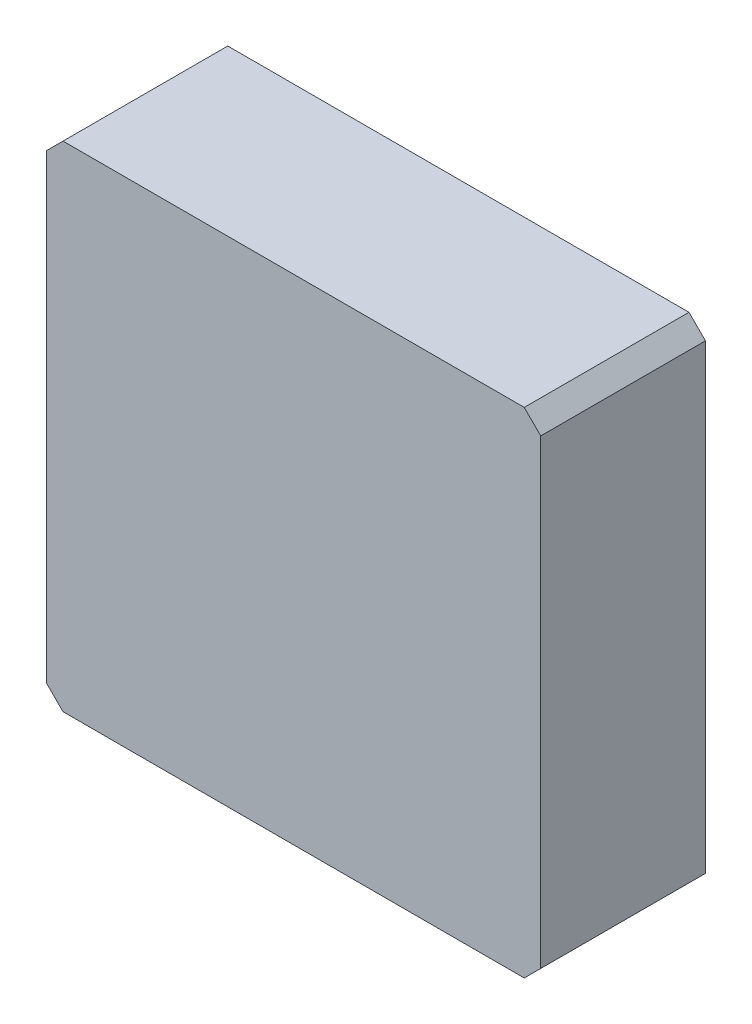
SolidWorks part; units mm, degrees
ref_plane "前视基准面" through (0, 0, 0) normal (0, 0, 1) x (1, 0, 0)
ref_plane "上视基准面" through (0, 0, 0) normal (0, 1, 0) x (1, 0, 0)
ref_plane "右视基准面" through (0, 0, 0) normal (1, 0, 0) x (0, 0, -1)
ref_plane "基准面4" through (0, 0, -5) normal (0, 0, -1) x (-1, 0, 0)
sketch "草图1" plane through (0, 0, -5) normal (0, 0, -1) x (-1, 0, 0)
  line L0 (-15, -14) -> (-14, -15)
  line L1 (-14, -15) -> (14, -15)
  line L2 (14, -15) -> (15, -14)
  line L3 (15, -14) -> (15, 14)
  line L4 (15, 14) -> (14, 15)
  line L5 (14, 15) -> (-14, 15)
  line L6 (-14, 15) -> (-15, 14)
  line L7 (-15, 14) -> (-15, -14)
extrude "凸台-拉伸1" add sketch "草图1" against normal blind 10
